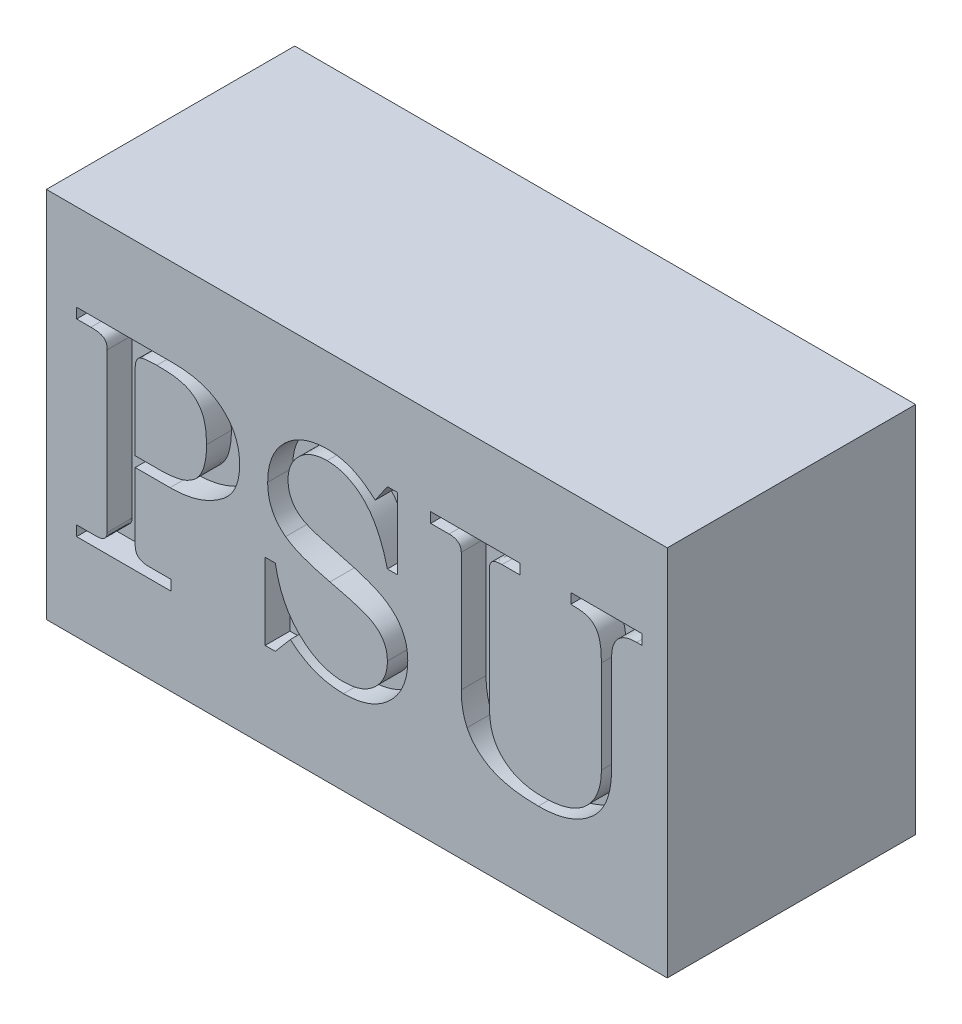
SolidWorks part; units mm, degrees
ref_plane "Front Plane" through (0, 0, 0) normal (0, 0, 1) x (1, 0, 0)
ref_plane "Top Plane" through (0, 0, 0) normal (0, 1, 0) x (1, 0, 0)
ref_plane "Right Plane" through (0, 0, 0) normal (1, 0, 0) x (0, 0, -1)
sketch "Sketch1" plane through (0, 0, 0) normal (0, 0, 1) x (1, 0, 0)
  line L1 (-62.5, 37.5) -> (62.5, 37.5)
  line L2 (-62.5, 37.5) -> (-62.5, -37.5)
  line L3 (-62.5, -37.5) -> (62.5, -37.5)
  line L4 (62.5, 37.5) -> (62.5, -37.5)
  line L5 (-62.5, 37.5) -> (62.5, -37.5) construction
  line L6 (-62.5, -37.5) -> (62.5, 37.5) construction
  point P0 (0, 0)
  dimension "D1" = 75
  dimension "D2" = 125
extrude "Boss-Extrude1" add sketch "Sketch1" along normal blind 50
sketch "Sketch2" plane through (0, 0, 50) normal (0, 0, 1) x (1, 0, 0)
  line L0 (-62.5, -20) -> (62.5, -20) construction
  line L1 (-62.5, 37.5) -> (-62.5, -37.5) construction
  line L2 (62.5, -37.5) -> (62.5, 37.5) construction
  text T0 "PSU" font "Century Schoolbook" height 40
  dimension "D1" = 20
extrude "Cut-Extrude1" cut sketch "Sketch2" against normal blind 5
